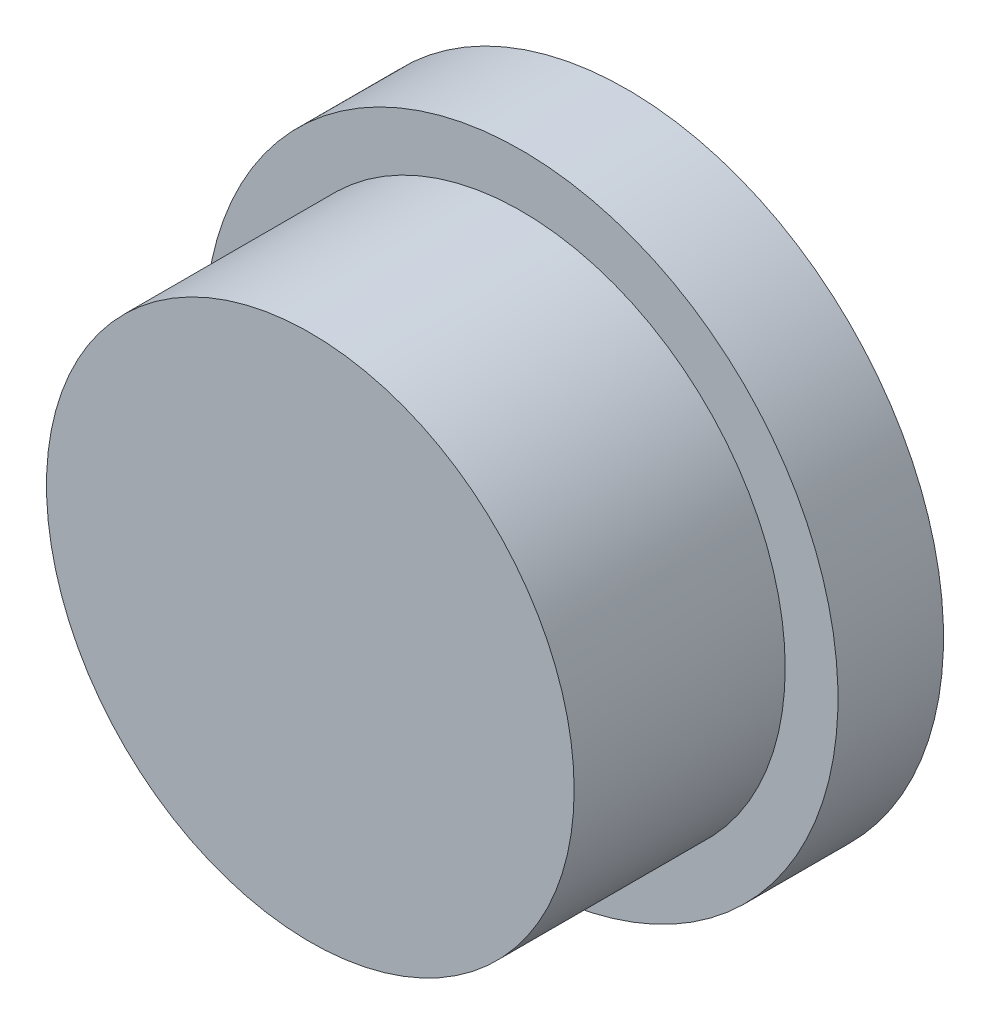
SolidWorks part; units mm, degrees
ref_plane "前视基准面" through (0, 0, 0) normal (0, 0, 1) x (1, 0, 0)
ref_plane "上视基准面" through (0, 0, 0) normal (0, 1, 0) x (1, 0, 0)
ref_plane "右视基准面" through (0, 0, 0) normal (1, 0, 0) x (0, 0, -1)
sketch "草图1" plane through (0, 0, 0) normal (0, 0, 1) x (1, 0, 0)
  circle A0 centre (0, 0) radius 2.5
extrude "凸台-拉伸1" add sketch "草图1" along normal blind 2
sketch "草图2" plane through (0, 0, 0) normal (0, 0, -1) x (-1, 0, 0)
  circle A0 centre (0, 0) radius 3
extrude "凸台-拉伸2" add sketch "草图2" along normal blind 1
